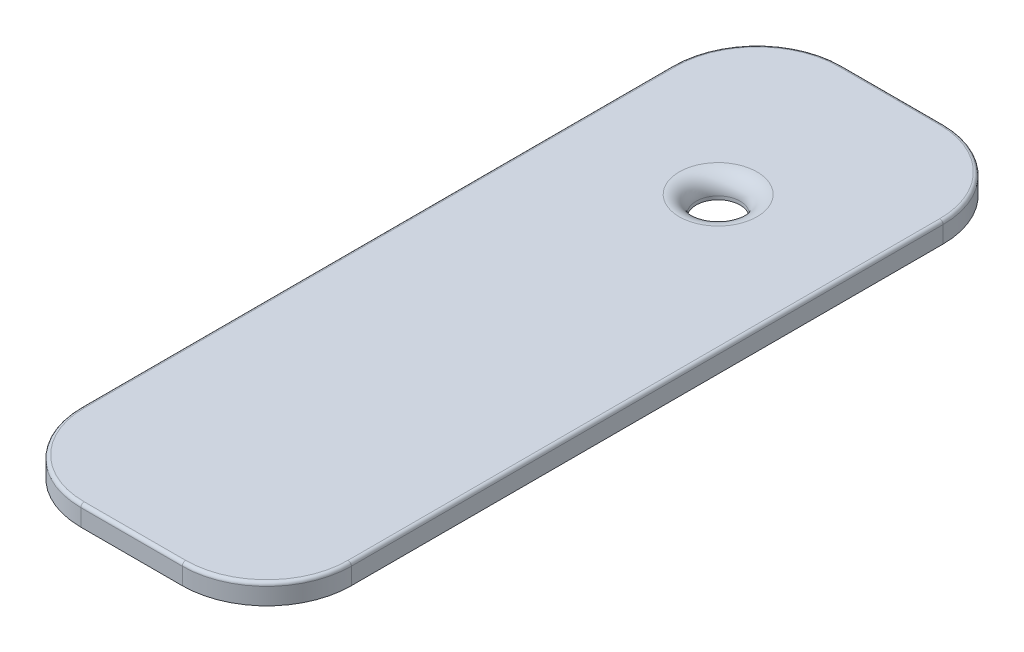
SolidWorks part; units mm, degrees
ref_plane "前视基准面" through (0, 0, 0) normal (0, 0, 1) x (1, 0, 0)
ref_plane "上视基准面" through (0, 0, 0) normal (0, 1, 0) x (1, 0, 0)
ref_plane "右视基准面" through (0, 0, 0) normal (1, 0, 0) x (0, 0, -1)
sketch "草图1" plane through (0, 0, 0) normal (0, 1, 0) x (1, 0, 0)
  line L1 (-11.4839, 51.5441) -> (18.5161, 51.5441)
  line L2 (-36.4839, 26.5441) -> (-36.4839, -148.4559)
  line L3 (-11.4839, -173.4559) -> (18.5161, -173.4559)
  line L4 (43.5161, 26.5441) -> (43.5161, -148.4559)
  arc A0 (18.5161, -173.4559) -> (43.5161, -148.4559) centre (18.5161, -148.4559) ccw
  arc A1 (-11.4839, -173.4559) -> (-36.4839, -148.4559) centre (-11.4839, -148.4559) cw
  arc A2 (43.5161, 26.5441) -> (18.5161, 51.5441) centre (18.5161, 26.5441) ccw
  arc A3 (-11.4839, 51.5441) -> (-36.4839, 26.5441) centre (-11.4839, 26.5441) ccw
  point P8 (-36.4839, -173.4559)
  point P11 (43.5161, 51.5441)
  point P14 (-36.4839, 51.5441)
  dimension "D3" = 25
  dimension "D1" = 225
  dimension "D2" = 80
extrude "凸台-拉伸1" add sketch "草图1" along normal blind 6
fillet "圆角1" radius 1 8 edges at (36.1938, 6, 166.1336) (3.5161, 6, 173.4559) (-29.1615, 6, 166.1336) (-36.4839, 6, 60.9559) (43.5161, 6, 60.9559) (36.1938, 6, -44.2218) (-29.1615, 6, -44.2218) (3.5161, 6, -51.5441)
sketch "草图2" plane through (0, 6, 0) normal (0, 1, 0) x (1, 0, 0)
  circle A0 centre (3.5161, 0) radius 6.5
  dimension "D1" = 13
extrude "切除-拉伸1" cut sketch "草图2" against normal through all
fillet "圆角2" radius 5 1 edges at (3.5161, 6, 6.5)
